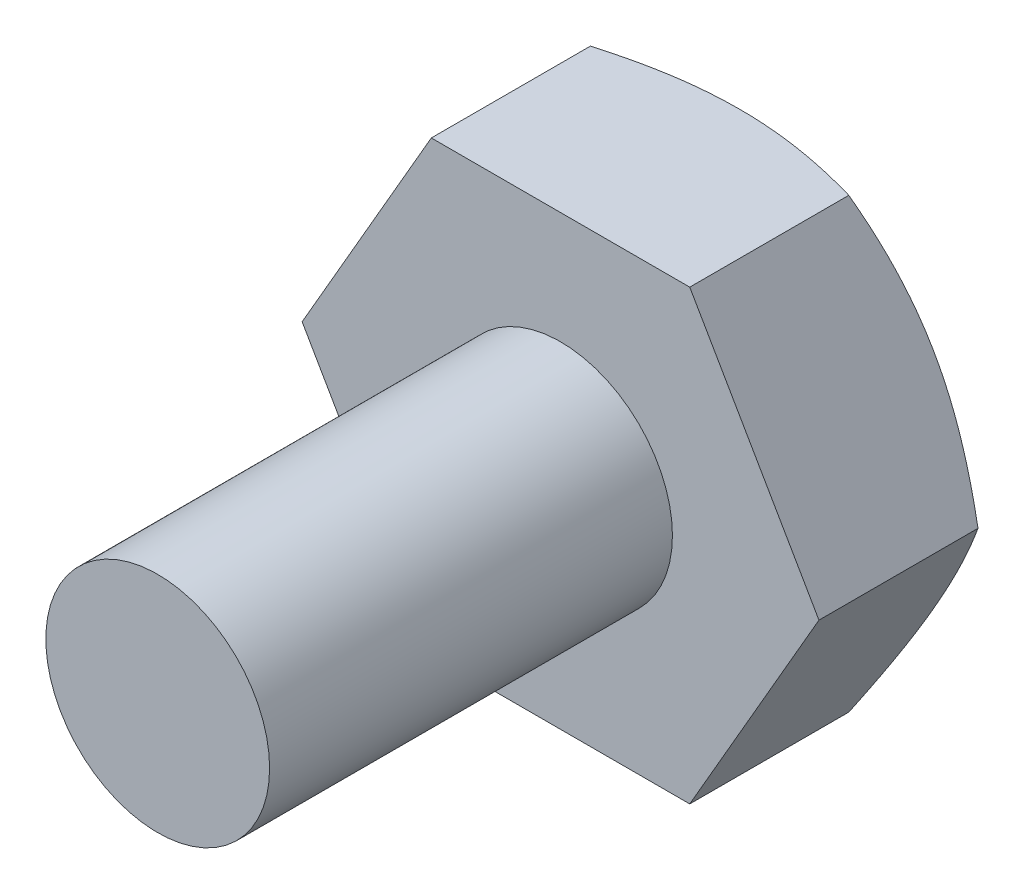
SolidWorks part; units mm, degrees
ref_plane "Ön Düzlem" through (0, 0, 0) normal (0, 0, 1) x (1, 0, 0)
ref_plane "Üst Düzlem" through (0, 0, 0) normal (0, 1, 0) x (1, 0, 0)
ref_plane "Sağ Düzlem" through (0, 0, 0) normal (1, 0, 0) x (0, 0, -1)
sketch "Çizim1" plane through (0, 0, 0) normal (0, 0, 1) x (1, 0, 0)
  line L1 (5.7735, 0) -> (2.8868, 5)
  line L2 (2.8868, 5) -> (-2.8868, 5)
  line L3 (-2.8868, 5) -> (-5.7735, 0)
  line L4 (-5.7735, 0) -> (-2.8868, -5)
  line L5 (-2.8868, -5) -> (2.8868, -5)
  line L6 (2.8868, -5) -> (5.7735, 0)
  circle A0 centre (0, 0) radius 5 construction
  dimension "D1" = 10
extrude "Yükseklik-Ekstrüzyon1" add sketch "Çizim1" along normal blind 4
sketch "Çizim2" plane through (0, 0, 4) normal (0, 0, 1) x (1, 0, 0)
  circle A0 centre (0, 0) radius 2.5
  dimension "D1" = 5
extrude "Yükseklik-Ekstrüzyon2" add sketch "Çizim2" along normal blind 9
cosmetic thread "Kozmetik Diş Açma1" parameters "D2"=4.11
sketch "Çizim3" plane through (0, 0, 0) normal (0, 0, -1) x (-1, 0, 0)
  circle A0 centre (0, 0) radius 5
extrude "Kes-Ekstrüzyon1" cut sketch "Çizim3" against normal blind 10 draft 60 flip side to cut
